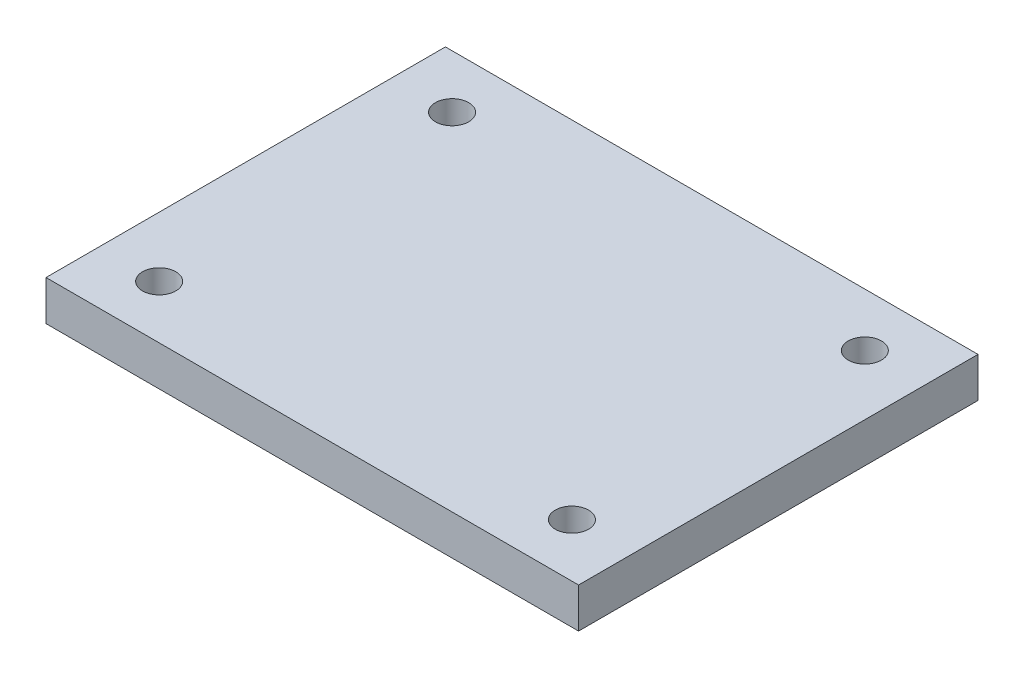
SolidWorks part; units mm, degrees
ref_plane "前视基准面" through (0, 0, 0) normal (0, 0, 1) x (1, 0, 0)
ref_plane "上视基准面" through (0, 0, 0) normal (0, 1, 0) x (1, 0, 0)
ref_plane "右视基准面" through (0, 0, 0) normal (1, 0, 0) x (0, 0, -1)
other "Configuration Table"
sketch "草图1" plane through (0, 0, 0) normal (0, 1, 0) x (1, 0, 0)
  line L1 (-20, 15) -> (20, 15)
  line L2 (-20, 15) -> (-20, -15)
  line L3 (-20, -15) -> (20, -15)
  line L4 (20, 15) -> (20, -15)
  line L5 (-20, 15) -> (20, -15) construction
  line L6 (-20, -15) -> (20, 15) construction
  point P0 (0, 0)
  dimension "D1" = 40
  dimension "D2" = 30
extrude "凸台-拉伸1" add sketch "草图1" along normal blind 3
sketch "草图2" plane through (0, 3, 0) normal (0, 1, 0) x (1, 0, 0)
  line L1 (-15.5, 11) -> (15.5, 11) construction
  line L2 (-15.5, 11) -> (-15.5, -11) construction
  line L3 (-15.5, -11) -> (15.5, -11) construction
  line L4 (15.5, 11) -> (15.5, -11) construction
  line L5 (-15.5, 11) -> (15.5, -11) construction
  line L6 (-15.5, -11) -> (15.5, 11) construction
  circle A0 centre (15.5, 11) radius 1.25
  circle A1 centre (-15.5, 11) radius 1.25
  circle A2 centre (-15.5, -11) radius 1.25
  circle A3 centre (15.5, -11) radius 1.25
  point P0 (0, 0)
  dimension "D1" = 2.5
  dimension "D2" = 31
  dimension "D3" = 22
extrude "切除-拉伸1" cut sketch "草图2" against normal blind 10
